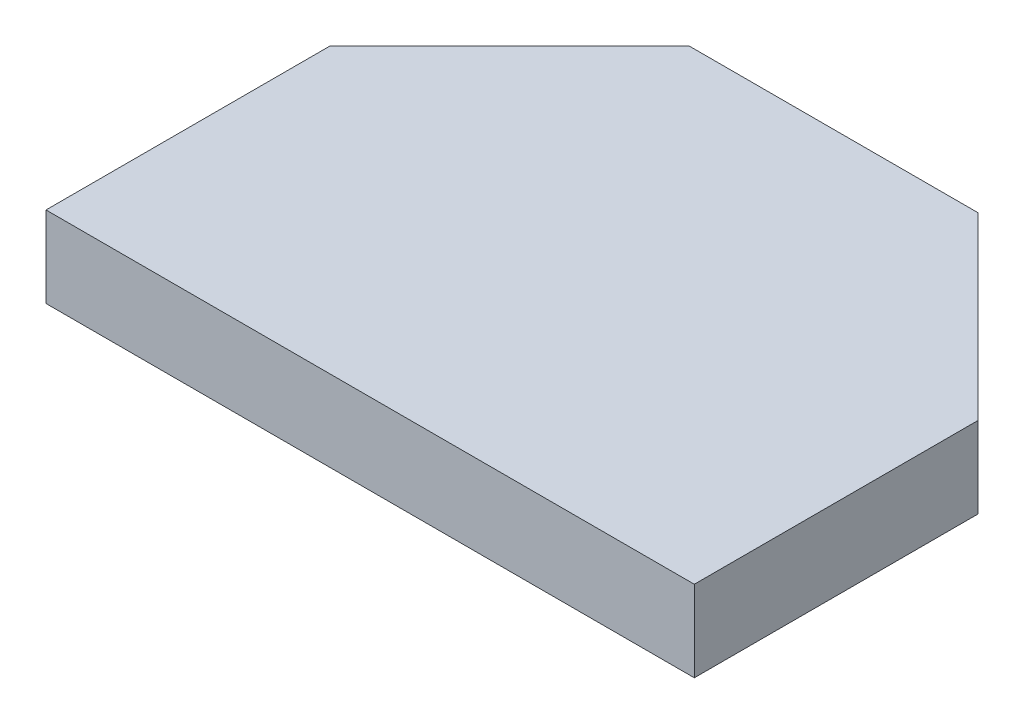
SolidWorks part; units mm, degrees
ref_plane "Front Plane" through (0, 0, 0) normal (0, 0, 1) x (1, 0, 0)
ref_plane "Top Plane" through (0, 0, 0) normal (0, 1, 0) x (1, 0, 0)
ref_plane "Right Plane" through (0, 0, 0) normal (1, 0, 0) x (0, 0, -1)
sketch "Sketch1" plane through (0, 0, 0) normal (0, 1, 0) x (1, 0, 0)
  line L0 (0, 0) -> (101.6, 0)
  line L1 (0, 0) -> (0, 44.45)
  line L2 (101.6, 0) -> (101.6, 44.45)
  line L3 (0, 44.45) -> (28.198, 72.648)
  line L4 (101.6, 44.45) -> (73.406, 72.652)
  line L5 (73.406, 72.652) -> (28.198, 72.648)
  dimension "D1" = 101.6
  dimension "D2" = 44.45
  dimension "D3" = 44.45
  dimension "D4" = 39.878
  dimension "D5" = 28.198
  dimension "D6" = 28.194
extrude "Boss-Extrude1" add sketch "Sketch1" along normal blind 12.7
sketch "Sketch2" plane through (0, 12.7, 0) normal (0, 1, 0) x (1, 0, 0)
  line L0 (0, 10.16) -> (101.6, 10.16)
  line L1 (25.4, 10.16) -> (25.4, 0)
  line L2 (50.8, 10.16) -> (50.8, 0)
  line L3 (76.2, 10.16) -> (76.2, 0)
  line L4 (0, 44.45) -> (0, 0) construction
  line L5 (101.6, 0) -> (101.6, 44.45) construction
  line L6 (0, 0) -> (101.6, 0) construction
  line L7 (0, 20.32) -> (101.6, 20.32)
  line L8 (0, 30.48) -> (101.6, 30.48)
  line L9 (0, 40.64) -> (101.6, 40.64)
  line L10 (6.35, 50.8) -> (95.2518, 50.8)
  line L11 (28.198, 72.648) -> (0, 44.45) construction
  line L12 (16.51, 60.96) -> (85.0947, 60.96)
  line L13 (101.6, 44.45) -> (73.406, 72.652) construction
  line L14 (12.7, 20.32) -> (12.7, 10.16)
  line L15 (38.1, 20.32) -> (38.1, 10.16)
  line L16 (63.5, 10.16) -> (63.5, 20.32)
  line L17 (88.9, 20.32) -> (88.9, 10.16)
  line L18 (25.4, 20.32) -> (25.4, 30.48)
  line L19 (50.8, 20.32) -> (50.8, 30.48)
  line L20 (76.2, 20.32) -> (76.2, 30.48)
  line L21 (88.9, 30.48) -> (88.9, 40.64)
  line L22 (63.5, 30.48) -> (63.5, 40.64)
  line L23 (38.1, 30.48) -> (38.1, 40.64)
  line L24 (12.7, 30.48) -> (12.7, 40.64)
  line L25 (25.4, 40.64) -> (25.4, 50.8)
  line L26 (50.8, 40.64) -> (50.8, 50.8)
  line L27 (76.2, 40.64) -> (76.2, 50.8)
  line L28 (12.7, 50.8) -> (12.7, 57.15)
  line L29 (38.1, 50.8) -> (38.1, 60.96)
  line L30 (63.5, 50.8) -> (63.5, 60.96)
  line L31 (88.9, 50.8) -> (88.9, 57.1536)
  line L32 (26.67, 71.12) -> (74.9376, 71.12)
  line L33 (25.4, 60.96) -> (25.4, 69.85)
  line L34 (50.8023, 60.96) -> (50.8038, 71.12)
  line L35 (76.2, 60.96) -> (76.2, 69.8572)
  line L36 (38.1, 71.12) -> (38.1, 72.6489)
  line L37 (73.406, 72.652) -> (28.198, 72.648) construction
  line L38 (63.5, 71.12) -> (63.5, 72.6511)
  dimension "D1" = 10.16
  dimension "D2" = 10.16
  dimension "D3" = 10.16
  dimension "D4" = 10.16
  dimension "D5" = 10.16
  dimension "D6" = 10.16
  dimension "D7" = 25.4
  dimension "D8" = 25.4
  dimension "D9" = 25.4
  dimension "D10" = 12.7
  dimension "D11" = 25.4
  dimension "D12" = 25.4
  dimension "D13" = 25.4
ref_plane "Plane1" through (0, 12.7, 0) normal (0, 0, 1) x (1, 0, 0)
